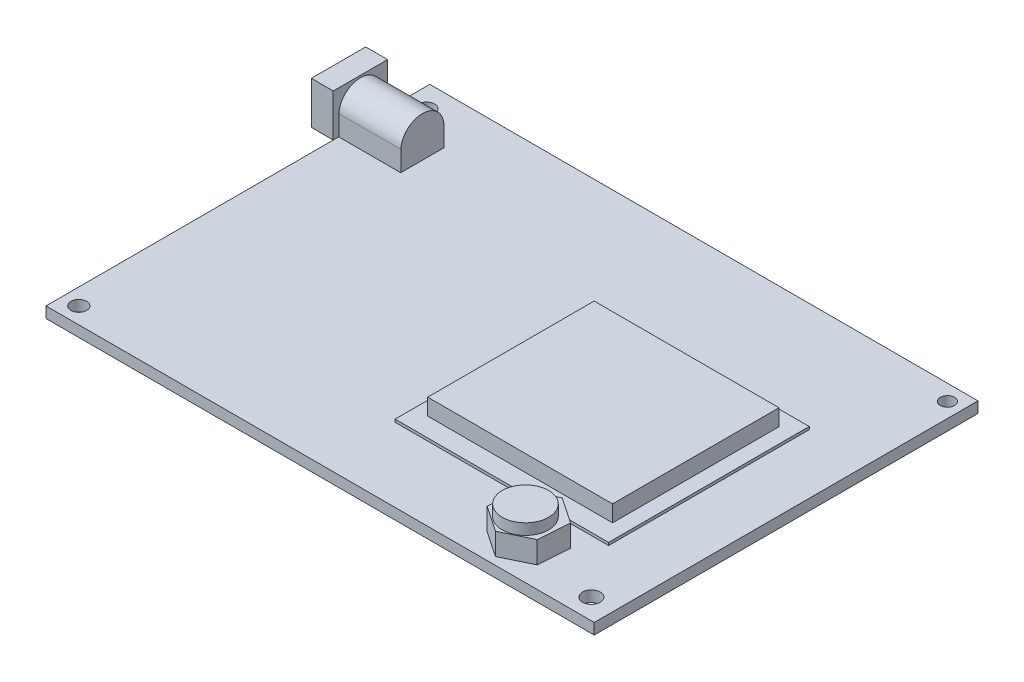
SolidWorks part; units mm, degrees
ref_plane "Front Plane" through (0, 0, 0) normal (0, 0, 1) x (1, 0, 0)
ref_plane "Top Plane" through (0, 0, 0) normal (0, 1, 0) x (1, 0, 0)
ref_plane "Right Plane" through (0, 0, 0) normal (1, 0, 0) x (0, 0, -1)
sketch "Sketch1" plane through (0, 0, 0) normal (0, 1, 0) x (1, 0, 0)
  line L1 (-50, 35) -> (50, 35)
  line L2 (-50, 35) -> (-50, -35)
  line L3 (-50, -35) -> (50, -35)
  line L4 (50, 35) -> (50, -35)
  line L5 (-50, 35) -> (50, -35) construction
  line L6 (-50, -35) -> (50, 35) construction
  point P0 (0, 0)
  dimension "D1" = 100
  dimension "D2" = 70
extrude "Boss-Extrude2" add sketch "Sketch1" along normal blind 2
sketch "Sketch2" plane through (0, 2, 0) normal (0, 1, 0) x (1, 0, 0)
  circle A0 centre (-46.4396, 30.8143) radius 1.5125
extrude "Cut-Extrude3" cut sketch "Sketch2" against normal blind 3
sketch "Sketch3" plane through (0, 2, 0) normal (0, 1, 0) x (1, 0, 0)
  circle A0 centre (-47.0041, -32.0089) radius 1.4353
extrude "Cut-Extrude4" cut sketch "Sketch3" against normal blind 3
sketch "Sketch4" plane through (0, 2, 0) normal (0, 1, 0) x (1, 0, 0)
  circle A0 centre (47.3029, 32.1171) radius 1.3013
extrude "Cut-Extrude5" cut sketch "Sketch4" against normal blind 3
sketch "Sketch5" plane through (0, 2, 0) normal (0, 1, 0) x (1, 0, 0)
  circle A0 centre (45.7471, -31.2677) radius 1.6163
extrude "Cut-Extrude6" cut sketch "Sketch5" against normal blind 3
sketch "Sketch6" plane through (0, 2, 0) normal (0, 1, 0) x (1, 0, 0)
  line L1 (-55.9813, 26.2511) -> (-38.6852, 26.2511)
  line L2 (-55.9813, 26.2511) -> (-55.9813, 18.3944)
  line L3 (-55.9813, 18.3944) -> (-38.6852, 18.3944)
  line L4 (-38.6852, 26.2511) -> (-38.6852, 18.3944)
  line L5 (-55.9813, 26.2511) -> (-38.6852, 18.3944) construction
  line L6 (-55.9813, 18.3944) -> (-38.6852, 26.2511) construction
  point P0 (-47.3333, 22.3227)
extrude "Boss-Extrude3" add sketch "Sketch6" along normal blind 7.5
sketch "Sketch13" plane through (-55.9813, 0, 0) normal (-1, 0, 0) x (0, 0, 1)
  line L0 (-26.2682, 5.8037) -> (-26.2511, 9.5)
  line L1 (-26.2511, 9.5) -> (-26.2511, 2) construction
  line L2 (-26.2511, 9.5) -> (-18.3944, 9.5) construction
  line L3 (-26.2511, 9.5) -> (-18.3944, 9.5)
  line L4 (-18.3944, 9.5) -> (-18.3842, 5.4209)
  arc A0 (-18.3842, 5.4209) -> (-26.2682, 5.8037) centre (-22.3355, 5.4209) ccw
  line M6 (-18.3944, 2) -> (-18.3944, 9.5)
  line M7 (-18.3944, 9.5) -> (-26.2511, 9.5)
  line M8 (-26.2511, 9.5) -> (-26.2511, 2)
extrude "Cut-Extrude14" cut sketch "Sketch13" against normal blind 19 contours A0 M6 M7 M8
sketch "Sketch14" plane through (0, 2, 0) normal (0, -1, 0) x (-1, 0, 0)
  line L0 (49.9835, 17.6291) -> (49.9835, 26.8299)
  line L1 (49.9835, 26.8299) -> (57.1695, 26.8299)
  line L2 (57.1695, 26.8299) -> (57.9114, 13.4731)
  line L3 (57.9114, 13.4731) -> (49.9835, 17.6291)
extrude "Cut-Extrude15" cut sketch "Sketch14" against normal blind 19
sketch "Sketch15" plane through (-49.9835, 0, 0) normal (-1, 0, 0) x (0, 0, 1)
  line L1 (-27.2943, 9.7698) -> (-17.3784, 9.7698)
  line L2 (-27.2943, 9.7698) -> (-27.2943, 2.0154)
  line L3 (-27.2943, 2.0154) -> (-17.3784, 2.0154)
  line L4 (-17.3784, 9.7698) -> (-17.3784, 2.0154)
  line L5 (-27.2943, 9.7698) -> (-17.3784, 2.0154) construction
  line L6 (-27.2943, 2.0154) -> (-17.3784, 9.7698) construction
  point P0 (-22.3364, 5.8926)
extrude "Boss-Extrude6" add sketch "Sketch15" along normal blind 4
sketch "Sketch16" plane through (-53.9835, 0, 0) normal (-1, 0, 0) x (0, 0, 1)
  circle A0 centre (-22.3589, 5.7648) radius 2.635
extrude "Cut-Extrude16" cut sketch "Sketch16" against normal blind 7
sketch "Sketch17" plane through (-46.9835, 0, 0) normal (-1, 0, 0) x (0, 0, 1)
  circle A0 centre (-22.3201, 5.9462) radius 0.6327
extrude "Boss-Extrude7" add sketch "Sketch17" along normal blind 7
sketch "Sketch18" plane through (0, 2, 0) normal (0, 1, 0) x (1, 0, 0)
  line L1 (39.1657, 15.0552) -> (0.221, 15.0552)
  line L2 (39.1657, 15.0552) -> (39.1657, -21.5457)
  line L3 (39.1657, -21.5457) -> (0.221, -21.5457)
  line L4 (0.221, 15.0552) -> (0.221, -21.5457)
  line L5 (39.1657, 15.0552) -> (0.221, -21.5457) construction
  line L6 (39.1657, -21.5457) -> (0.221, 15.0552) construction
  point P0 (19.6934, -3.2452)
  point P5 (19.6934, -3.2452)
extrude "Boss-Extrude8" add sketch "Sketch18" along normal blind 0.5
sketch "Sketch19" plane through (0, 2.5, 0) normal (0, 1, 0) x (1, 0, 0)
  line L1 (36.4389, 12.2594) -> (2.7262, 12.2594)
  line L2 (36.4389, 12.2594) -> (36.4389, -18.1016)
  line L3 (36.4389, -18.1016) -> (2.7262, -18.1016)
  line L4 (2.7262, 12.2594) -> (2.7262, -18.1016)
  line L5 (36.4389, 12.2594) -> (2.7262, -18.1016) construction
  line L6 (36.4389, -18.1016) -> (2.7262, 12.2594) construction
  point P0 (19.5825, -2.9211)
  point P5 (19.5825, -2.8676)
extrude "Boss-Extrude9" add sketch "Sketch19" along normal blind 3
sketch "Sketch20" plane through (0, 2, 0) normal (0, 1, 0) x (1, 0, 0)
  circle A0 centre (30.9989, -28.5436) radius 4.2337
  point P2 (30.9989, -28.5436)
extrude "Boss-Extrude10" add sketch "Sketch20" along normal blind 6
sketch "Sketch21" plane through (0, 2, 0) normal (0, 1, 0) x (1, 0, 0)
  line L1 (35.7064, -31.1112) -> (36.1118, -25.4373)
  line L2 (36.1118, -25.4373) -> (31.4009, -22.2493)
  line L3 (31.4009, -22.2493) -> (26.2844, -24.7351)
  line L4 (26.2844, -24.7351) -> (25.879, -30.4089)
  line L5 (25.879, -30.4089) -> (30.5899, -33.597)
  line L6 (30.5899, -33.597) -> (35.7064, -31.1112)
  circle A0 centre (30.9954, -27.9231) radius 4.9262 construction
extrude "Boss-Extrude11" add sketch "Sketch21" along normal blind 4
